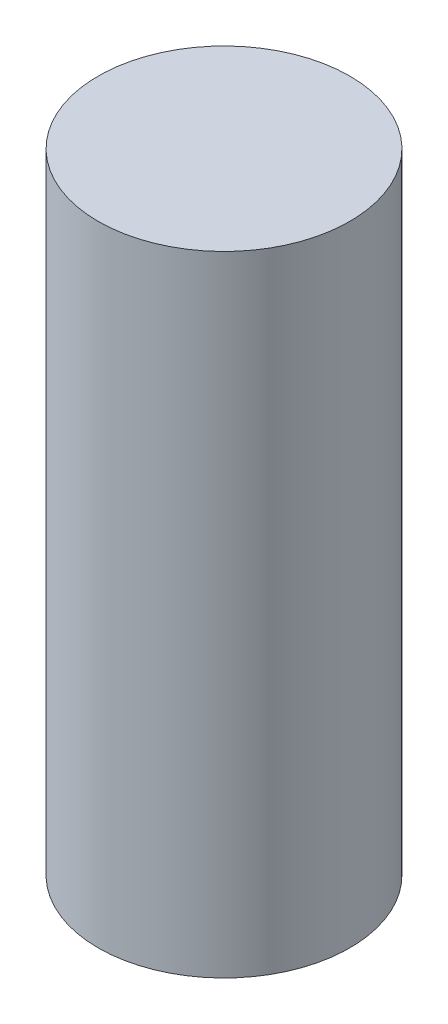
SolidWorks part; units mm, degrees
material "Roble"
ref_plane "Alzado" through (0, 0, 0) normal (0, 0, 1) x (1, 0, 0)
ref_plane "Planta" through (0, 0, 0) normal (0, 1, 0) x (1, 0, 0)
ref_plane "Vista lateral" through (0, 0, 0) normal (1, 0, 0) x (0, 0, -1)
sketch "Croquis1" plane through (0, 0, 0) normal (0, 1, 0) x (1, 0, 0)
  circle A0 centre (0, 0) radius 2
  dimension "D1" = 4
extrude "Saliente-Extruir1" add sketch "Croquis1" along normal mid plane 10
